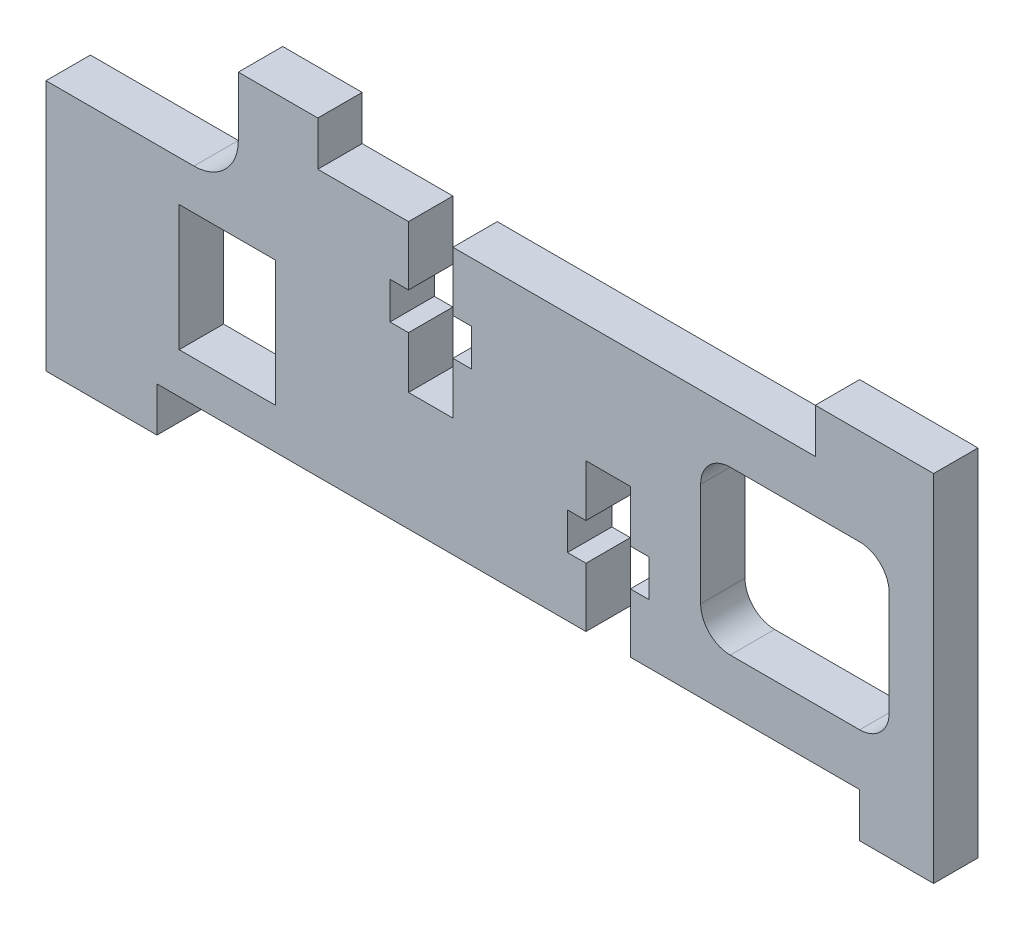
SolidWorks part; units mm, degrees
ref_plane "前视基准面" through (0, 0, 0) normal (0, 0, 1) x (1, 0, 0)
ref_plane "上视基准面" through (0, 0, 0) normal (0, 1, 0) x (1, 0, 0)
ref_plane "右视基准面" through (0, 0, 0) normal (1, 0, 0) x (0, 0, -1)
ref_plane "基准面1" through (0, 0, 3) normal (0, 0, 1) x (1, 0, 0)
sketch "草图1" plane through (0, 0, 3) normal (0, 0, 1) x (1, 0, 0)
  line L0 (9, -5.6664) -> (9, 2.8336)
  line L1 (9, 2.8336) -> (15.5, 2.8336)
  line L2 (15.5, 2.8336) -> (15.5, -5.6664)
  line L3 (15.5, -5.6664) -> (9, -5.6664)
  line L4 (56.9998, 4.0826) -> (56.9998, -2.9164)
  line L5 (54.9998, -4.9164) -> (46.2504, -4.9164)
  line L6 (44.2504, -2.9164) -> (44.2504, 4.0826)
  line L7 (46.2504, 6.0826) -> (54.9998, 6.0826)
  line L8 (7.4994, -8.4164) -> (36.5002, -8.4164)
  line L9 (36.5002, -8.4164) -> (36.5002, -4.4164)
  line L10 (36.5002, -4.4164) -> (35.2489, -4.4164)
  line L11 (35.2489, -4.4164) -> (35.2489, -1.9164)
  line L12 (35.2489, -1.9164) -> (36.5002, -1.9164)
  line L13 (36.5002, -1.9164) -> (36.5002, 1.5836)
  line L14 (36.5002, 1.5836) -> (39.5003, 1.5836)
  line L15 (39.5003, 1.5836) -> (39.5003, -1.9164)
  line L16 (39.5003, -1.9164) -> (40.7501, -1.9164)
  line L17 (40.7501, -1.9164) -> (40.7501, -4.4164)
  line L18 (40.7501, -4.4164) -> (39.5003, -4.4164)
  line L19 (39.5003, -4.4164) -> (39.5003, -8.4164)
  line L20 (39.5003, -8.4164) -> (54.9988, -8.4164)
  line L21 (54.9988, -8.4164) -> (54.9988, -11.4164)
  line L22 (54.9988, -11.4164) -> (59.9998, -11.4164)
  line L23 (59.9998, -11.4164) -> (59.9998, 12.5836)
  line L24 (59.9998, 12.5836) -> (51.9988, 12.5836)
  line L25 (51.9988, 12.5836) -> (51.9988, 9.5836)
  line L26 (51.9988, 9.5836) -> (27.5031, 9.5836)
  line L27 (27.5031, 9.5836) -> (27.5031, 5.5836)
  line L28 (27.5031, 5.5836) -> (28.7543, 5.5836)
  line L29 (28.7543, 5.5836) -> (28.7543, 3.0836)
  line L30 (28.7543, 3.0836) -> (27.5031, 3.0836)
  line L31 (27.5031, 3.0836) -> (27.5031, -0.4164)
  line L32 (27.5031, -0.4164) -> (24.503, -0.4164)
  line L33 (24.503, -0.4164) -> (24.503, 3.0836)
  line L34 (24.503, 3.0836) -> (23.2531, 3.0836)
  line L35 (23.2531, 3.0836) -> (23.2531, 5.5836)
  line L36 (23.2531, 5.5836) -> (24.503, 5.5836)
  line L37 (24.503, 5.5836) -> (24.503, 9.5836)
  line L38 (24.503, 9.5836) -> (18.3721, 9.5836)
  line L39 (18.3721, 9.5836) -> (18.3721, 12.5836)
  line L40 (18.3721, 12.5836) -> (12.9991, 12.5836)
  line L41 (12.9991, 12.5836) -> (12.9991, 8.5826)
  line L42 (9.9991, 5.5826) -> (0, 5.5826)
  line L43 (0, 5.5826) -> (0, -11.4164)
  line L44 (0, -11.4164) -> (7.4994, -11.4164)
  line L45 (7.4994, -11.4164) -> (7.4994, -8.4164)
  arc A0 (56.9998, -2.9164) -> (54.9998, -4.9164) centre (54.9998, -2.9164) cw
  arc A1 (46.2504, -4.9164) -> (44.2504, -2.9164) centre (46.2504, -2.9164) cw
  arc A2 (44.2504, 4.0826) -> (46.2504, 6.0826) centre (46.2504, 4.0826) cw
  arc A3 (54.9998, 6.0826) -> (56.9998, 4.0826) centre (54.9998, 4.0826) cw
  arc A4 (12.9991, 8.5826) -> (9.9991, 5.5826) centre (9.9991, 8.5826) cw
extrude "凸台-拉伸1" add sketch "草图1" against normal blind 3
